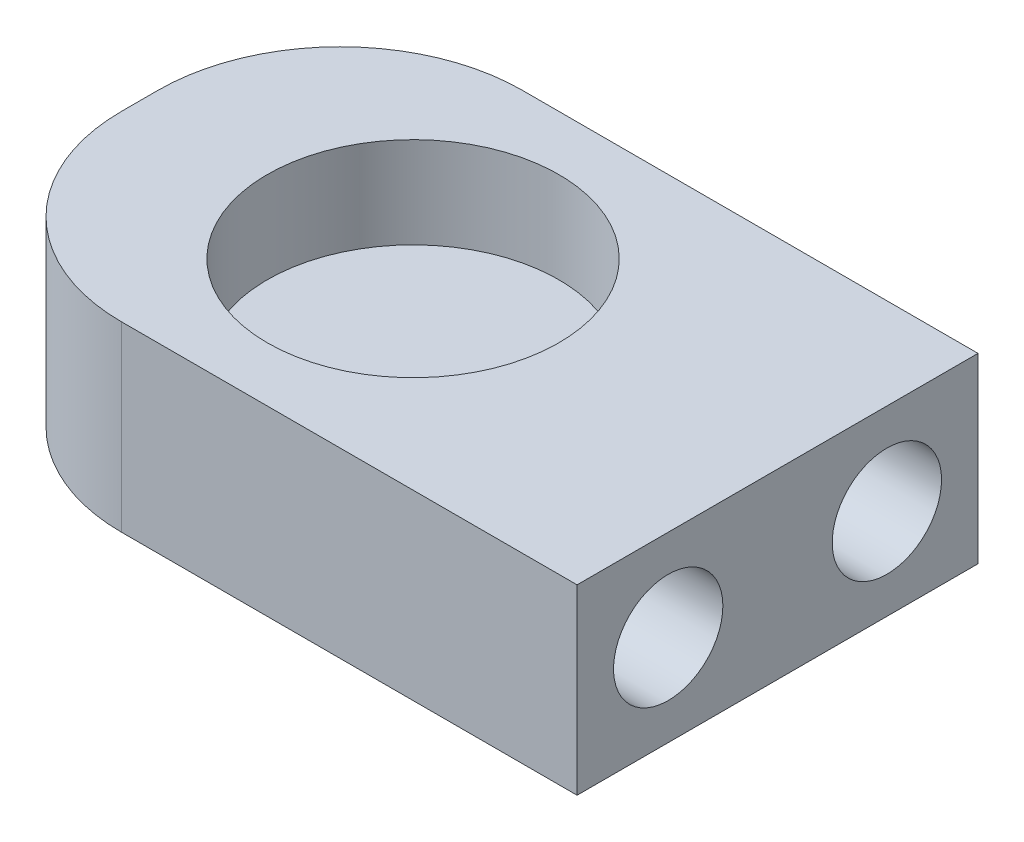
SolidWorks part; units mm, degrees
ref_plane "Front Plane" through (0, 0, 0) normal (0, 0, 1) x (1, 0, 0)
ref_plane "Top Plane" through (0, 0, 0) normal (0, 1, 0) x (1, 0, 0)
ref_plane "Right Plane" through (0, 0, 0) normal (1, 0, 0) x (0, 0, -1)
sketch "Sketch1" plane through (0, 0, 0) normal (0, 1, 0) x (1, 0, 0)
  line L1 (-17.5, 11) -> (17.5, 11)
  line L2 (-17.5, 11) -> (-17.5, -11)
  line L3 (-17.5, -11) -> (17.5, -11)
  line L4 (17.5, 11) -> (17.5, -11)
  line L5 (-17.5, 11) -> (17.5, -11) construction
  line L6 (-17.5, -11) -> (17.5, 11) construction
  point P0 (0, 0)
  dimension "D1" = 22
  dimension "D2" = 35
extrude "Boss-Extrude1" add sketch "Sketch1" along normal blind 10
sketch "Sketch2" plane through (17.5, 0, 0) normal (1, 0, 0) x (0, 0, -1)
  line L0 (11, 10) -> (11, 0) construction
  line L1 (-11, 10) -> (11, 10) construction
  line L2 (-11, 10) -> (-11, 0) construction
  circle A0 centre (6, 5) radius 3
  circle A1 centre (-6, 5) radius 3
  dimension "D1" = 5
  dimension "D3" = 5
  dimension "D2" = 5
extrude "Cut-Extrude1" cut sketch "Sketch2" against normal blind 10
sketch "Sketch3" plane through (0, 10, 0) normal (0, 1, 0) x (1, 0, 0)
  line L0 (17.5, -11) -> (17.5, 11) construction
  circle A0 centre (-2.5, 0) radius 8
  point P2 (0, 0)
  dimension "D1" = 20
extrude "Cut-Extrude2" cut sketch "Sketch3" against normal blind 5
fillet "Fillet1" radius 10 2 edges at (-17.5, 5, -11) (-17.5, 5, 11)
